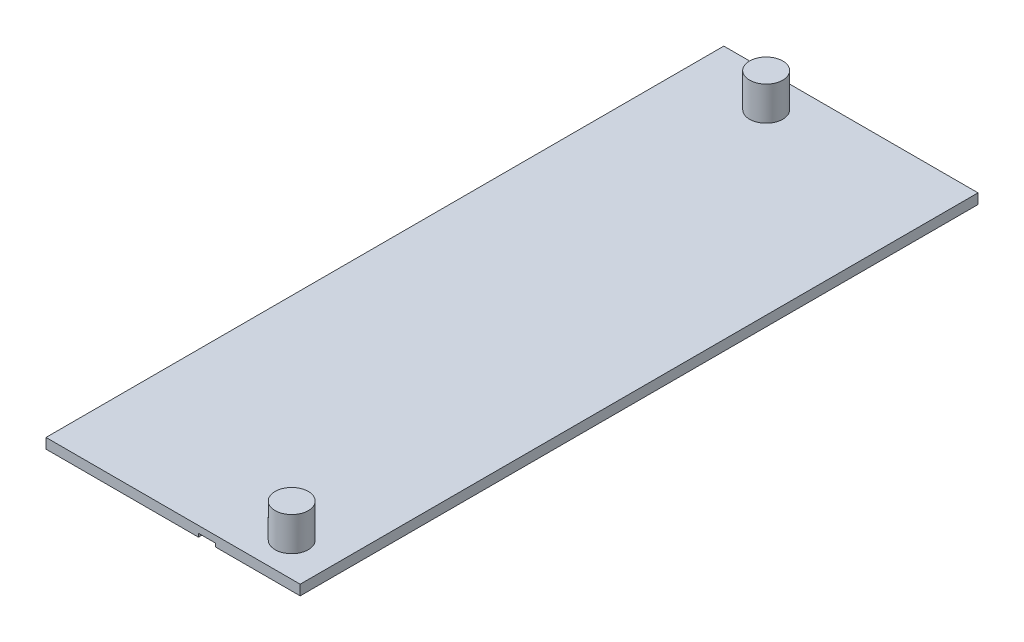
SolidWorks part; units mm, degrees
ref_plane "Front Plane" through (0, 0, 0) normal (0, 0, 1) x (1, 0, 0)
ref_plane "Top Plane" through (0, 0, 0) normal (0, 1, 0) x (1, 0, 0)
ref_plane "Right Plane" through (0, 0, 0) normal (1, 0, 0) x (0, 0, -1)
sketch "Sketch1" plane through (0, 0, 0) normal (0, 0, 1) x (1, 0, 0)
  line L1 (0, 0) -> (75, 0)
  line L2 (0, 0) -> (0, 3)
  line L3 (0, 3) -> (75, 3)
  line L4 (75, 0) -> (75, 3)
  dimension "D1" = 3
  dimension "D2" = 75
extrude "Boss-Extrude1" add sketch "Sketch1" along normal blind 200
sketch "Sketch2" plane through (0, 3, 0) normal (0, 1, 0) x (1, 0, 0)
  line L1 (225, 0) -> (0, 0)
  line L2 (225, 0) -> (225, -200)
  line L3 (225, -200) -> (0, -200)
  line L4 (0, 0) -> (0, -200)
  line L5 (212.5, -200) -> (12.5, -200)
  line L6 (212.5, -200) -> (212.5, 0)
  line L7 (212.5, 0) -> (12.5, 0)
  line L8 (12.5, -200) -> (12.5, 0)
  line L9 (75, -200) -> (0, -200) construction
  line L10 (75, 0) -> (0, 0) construction
  line L11 (75, -200) -> (75, 0) construction
  circle A0 centre (202.5, -190) radius 4.9
  circle A1 centre (162.5, -10) radius 4.9
  circle A2 centre (122.5, -190) radius 4.9
  circle A3 centre (82.5, -10) radius 4.9
  circle A4 centre (62.5, -190) radius 4.9
  circle A5 centre (22.5, -10) radius 4.9
  dimension "D4" = 10
  dimension "D5" = 10
  dimension "D6" = 9.8
  dimension "D7" = 9.8
  dimension "D8" = 10
  dimension "D9" = 40
  dimension "D11" = 10
  dimension "D12" = 10
  dimension "D13" = 80
  dimension "D14" = 80
  dimension "D15" = 10
  dimension "D16" = 10
  dimension "D17" = 60
  dimension "D18" = 60
  dimension "D19" = 9.8
  dimension "D20" = 9.8
  dimension "D21" = 9.8
  dimension "D22" = 9.8
  dimension "D1" = 225
  dimension "D2" = 12.5
  dimension "D3" = 12.5
  dimension "D10" = 150
extrude "Boss-Extrude2" add sketch "Sketch2" along normal blind 10 contours A4 | A5
sketch "Sketch3" plane through (0, 0, 0) normal (0, -1, 0) x (1, 0, 0)
  line L0 (4, 43) -> (11, 43)
  line L1 (4, 43) -> (4, 10)
  line L2 (4, 10) -> (11, 10)
  line L3 (11, 43) -> (11, 10)
  line L4 (4, 47) -> (11, 47)
  line L5 (4, 47) -> (4, 80)
  line L6 (4, 80) -> (11, 80)
  line L7 (11, 47) -> (11, 80)
  line L9 (0, 200) -> (0, 0) construction
  line L10 (19, 43) -> (26, 43)
  line L11 (19, 43) -> (19, 10)
  line L12 (19, 10) -> (26, 10)
  line L13 (26, 43) -> (26, 10)
  line L14 (19, 47) -> (26, 47)
  line L15 (19, 47) -> (19, 80)
  line L16 (19, 80) -> (26, 80)
  line L17 (26, 47) -> (26, 80)
  line L18 (34, 43) -> (41, 43)
  line L19 (34, 43) -> (34, 10)
  line L20 (34, 10) -> (41, 10)
  line L21 (41, 43) -> (41, 10)
  line L22 (34, 47) -> (41, 47)
  line L23 (34, 47) -> (34, 80)
  line L24 (34, 80) -> (41, 80)
  line L25 (41, 47) -> (41, 80)
  line L26 (49, 43) -> (56, 43)
  line L27 (49, 43) -> (49, 10)
  line L28 (49, 10) -> (56, 10)
  line L29 (56, 43) -> (56, 10)
  line L30 (49, 47) -> (56, 47)
  line L31 (49, 47) -> (49, 80)
  line L32 (49, 80) -> (56, 80)
  line L33 (56, 47) -> (56, 80)
  line L34 (64, 43) -> (71, 43)
  line L35 (64, 43) -> (64, 10)
  line L36 (64, 10) -> (71, 10)
  line L37 (71, 43) -> (71, 10)
  line L38 (64, 47) -> (71, 47)
  line L39 (64, 47) -> (64, 80)
  line L40 (64, 80) -> (71, 80)
  line L41 (71, 47) -> (71, 80)
  line L42 (0, 0) -> (75, 0) construction
  line L43 (0, 200) -> (75, 200) construction
  line L44 (45, 200) -> (50, 200)
  line L45 (45, 200) -> (45, 170)
  line L46 (45, 170) -> (50, 170)
  line L47 (50, 200) -> (50, 170)
  line L52 (45, 150) -> (50, 150)
  line L53 (45, 150) -> (45, 120)
  line L54 (45, 120) -> (50, 120)
  line L55 (50, 150) -> (50, 120)
  point P50 (47.5, 200)
  dimension "D1" = 70
  dimension "D2" = 33
  dimension "D3" = 33
  dimension "D4" = 7
  dimension "D5" = 7
  dimension "D6" = 4
  dimension "D7" = 4
  dimension "D9" = 10
  dimension "D10" = 47.5
  dimension "D11" = 5
  dimension "D12" = 30
  dimension "D8" = 5
  dimension "D13" = 2
extrude "Cut-Extrude1" cut sketch "Sketch3" against normal blind 1
